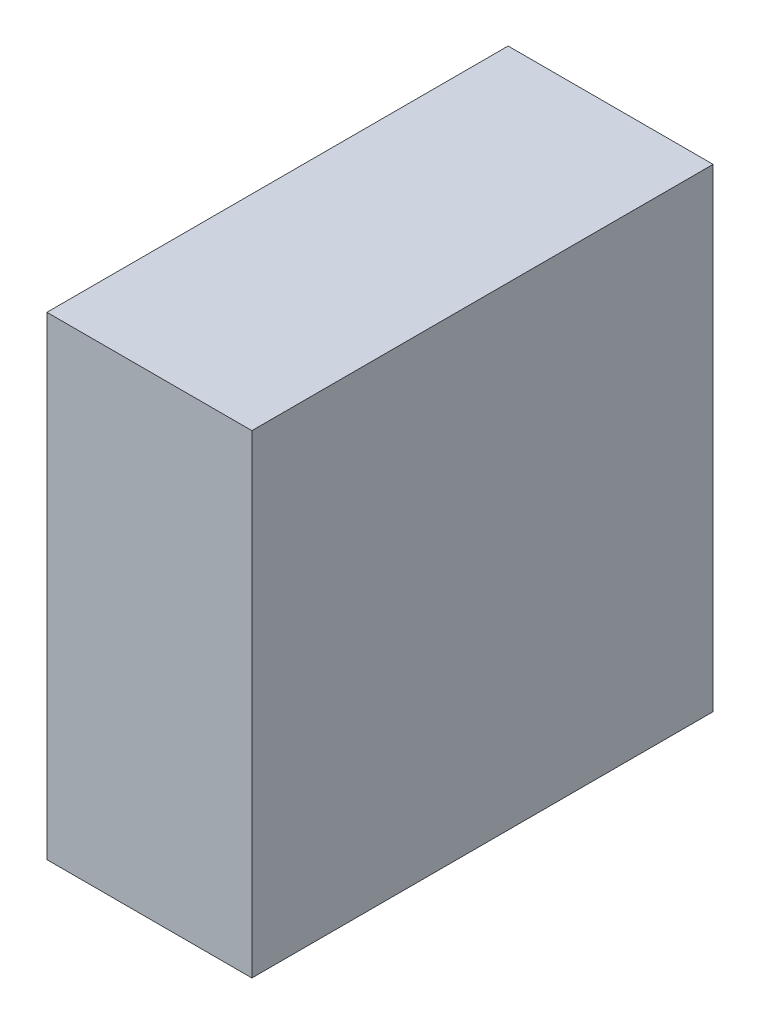
SolidWorks part; units mm, degrees
ref_plane "Front Plane" through (0, 0, 0) normal (1, 0, 0) x (0, 1, 0)
ref_plane "Top Plane" through (0, 0, 0) normal (0, 0, 1) x (0, 1, 0)
ref_plane "Right Plane" through (0, 0, 0) normal (0, 1, 0) x (-1, 0, 0)
sketch "Sketch1" plane through (0, 0, 0) normal (1, 0, 0) x (0, 1, 0)
  line L1 (9.25, -9) -> (-9.25, -9)
  line L2 (9.25, -9) -> (9.25, 9)
  line L3 (9.25, 9) -> (-9.25, 9)
  line L4 (-9.25, -9) -> (-9.25, 9)
  line L5 (9.25, -9) -> (-9.25, 9) construction
  line L6 (9.25, 9) -> (-9.25, -9) construction
  point P0 (0, 0)
  dimension "D1" = 18
  dimension "D2" = 18.5
extrude "Boss-Extrude1" add sketch "Sketch1" along normal mid plane 8
